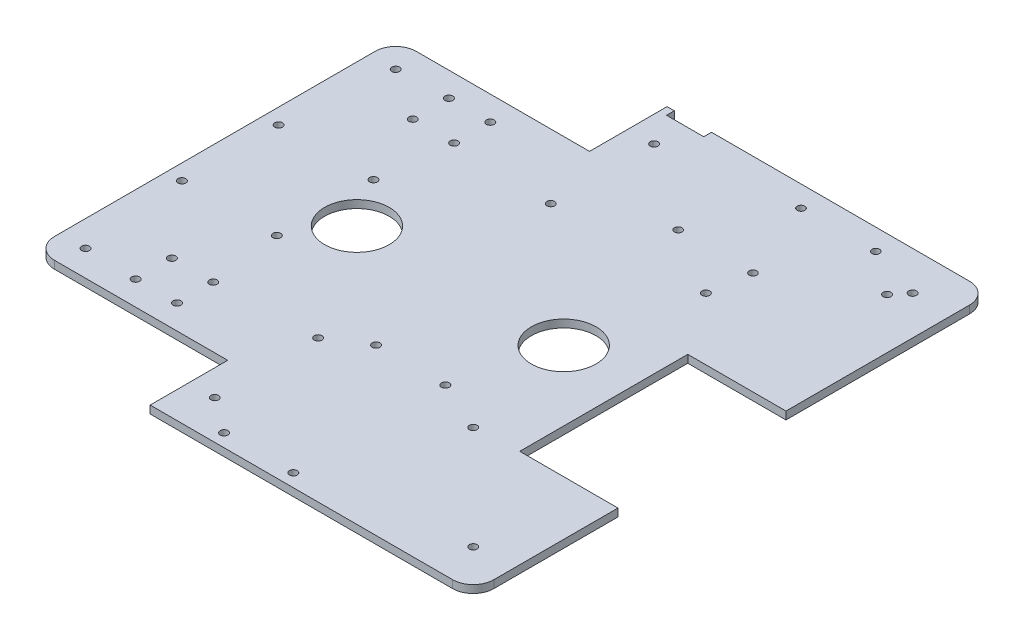
SolidWorks part; units mm, degrees
ref_plane "Front Plane" through (0, 0, 0) normal (0, 0, 1) x (1, 0, 0)
ref_plane "Top Plane" through (0, 0, 0) normal (0, 1, 0) x (1, 0, 0)
ref_plane "Right Plane" through (0, 0, 0) normal (1, 0, 0) x (0, 0, -1)
sketch "Sketch1" plane through (0, 0, 0) normal (0, 1, 0) x (1, 0, 0)
  line L1 (-100, 100) -> (100, 100)
  line L2 (-100, 100) -> (-100, -100)
  line L3 (-100, -100) -> (100, -100)
  line L4 (100, 100) -> (100, -100)
  line L5 (-100, 100) -> (100, -100) construction
  line L6 (-100, -100) -> (100, 100) construction
  point P0 (0, 0)
  dimension "D1" = 200
  dimension "D2" = 200
extrude "Boss-Extrude1" add sketch "Sketch1" along normal blind 3
sketch "Sketch4" plane through (0, 0, 0) normal (0, -1, 0) x (1, 0, 0)
  line L0 (100, 100) -> (100, -100) construction
  circle A0 centre (-15, 45) radius 1.5
  circle A1 centre (45, 45) radius 1.5
  circle A2 centre (45, -45) radius 1.5
  circle A3 centre (-15, -45) radius 1.5
  dimension "D1" = 3
  dimension "D2" = 3
  dimension "D3" = 3
  dimension "D4" = 3
  dimension "D8" = 55
  dimension "D5" = 60
  dimension "D6" = 90
  dimension "D7" = 45
extrude "Cut-Extrude4" cut sketch "Sketch4" against normal up to next
sketch "Sketch5" plane through (0, 0, 0) normal (0, -1, 0) x (1, 0, 0)
  line L1 (-100, -70) -> (-25, -70)
  line L2 (-100, -70) -> (-100, -100)
  line L3 (-100, -100) -> (-25, -100)
  line L4 (-25, -70) -> (-25, -100)
  line L5 (-100, -70) -> (-25, -100) construction
  line L6 (-100, -100) -> (-25, -70) construction
  line L8 (-100, 100) -> (-25, 100)
  line L9 (-100, 100) -> (-100, 70)
  line L10 (-100, 70) -> (-25, 70)
  line L11 (-25, 100) -> (-25, 70)
  line L12 (-100, 100) -> (-25, 70) construction
  line L13 (-100, 70) -> (-25, 100) construction
  point P0 (-62.5, -85)
  point P6 (-62.5, 85)
  dimension "D1" = 75
  dimension "D2" = 30
  dimension "D3" = 75
  dimension "D4" = 30
extrude "Cut-Extrude5" cut sketch "Sketch5" against normal up to next and the other way through all
sketch "Sketch3" plane through (0, 0, 0) normal (0, -1, 0) x (1, 0, 0)
  line L0 (-100, 70) -> (-25, 70) construction
  line L1 (-25, -70) -> (-100, -70) construction
  line L2 (-100, -70) -> (-100, 70) construction
  circle A0 centre (-70, -60.6) radius 1.5
  circle A1 centre (-70, -46.6) radius 1.5
  circle A2 centre (-54, -46.6) radius 1.5
  circle A3 centre (-54, -60.6) radius 1.5
  circle A4 centre (-70, 60.6) radius 1.5
  circle A5 centre (-54, 60.6) radius 1.5
  circle A6 centre (-70, 46.6) radius 1.5
  circle A7 centre (-54, 46.6) radius 1.5
  dimension "D1" = 3
  dimension "D2" = 3
  dimension "D3" = 3
  dimension "D4" = 3
  dimension "D5" = 3
  dimension "D6" = 3
  dimension "D7" = 3
  dimension "D8" = 3
  dimension "D9" = 16
  dimension "D10" = 14
  dimension "D11" = 14
  dimension "D12" = 9.4
  dimension "D13" = 9.4
  dimension "D14" = 30
extrude "Cut-Extrude6" cut sketch "Sketch3" against normal up to next
fillet "Fillet1" radius 8 4 edges at (100, 1.5, -100) (100, 1.5, 100) (-100, 1.5, 70) (-100, 1.5, -70)
sketch "Sketch6" plane through (0, 0, 0) normal (0, -1, 0) x (1, 0, 0)
  line L0 (-92, 70) -> (-25, 70) construction
  line L1 (-100, -62) -> (-100, 62) construction
  line L2 (-25, -70) -> (-92, -70) construction
  line L3 (-25, -100) -> (-25, -70) construction
  line L4 (92, -100) -> (-25, -100) construction
  line L5 (100, 92) -> (100, -92) construction
  line L6 (-25, 100) -> (92, 100) construction
  line L7 (-25, 70) -> (-25, 100) construction
  circle A0 centre (-90, 60) radius 1.5
  circle A1 centre (-90, -60) radius 1.5
  circle A2 centre (-15, -85) radius 1.5
  circle A3 centre (85, -85) radius 1.5
  circle A4 centre (85, 85) radius 1.5
  circle A5 centre (-15, 85) radius 1.5
  dimension "D1" = 3
  dimension "D2" = 3
  dimension "D3" = 3
  dimension "D4" = 3
  dimension "D5" = 3
  dimension "D6" = 3
  dimension "D7" = 10
  dimension "D8" = 10
  dimension "D9" = 10
  dimension "D10" = 10
  dimension "D11" = 10
  dimension "D12" = 15
  dimension "D13" = 15
  dimension "D14" = 15
  dimension "D15" = 15
  dimension "D16" = 10
extrude "Cut-Extrude7" cut sketch "Sketch6" against normal up to next
sketch "Sketch9" plane through (0, 3, 0) normal (0, 1, 0) x (1, 0, 0)
  line L0 (100, -92) -> (100, 92) construction
  point P0 (100, 0)
sketch "Sketch11" plane through (0, 0, 0) normal (0, 1, 0) x (1, 0, 0)
  line L0 (-25, -100) -> (92, -100) construction
  line L1 (62, -44) -> (100, -44)
  line L2 (62, -44) -> (62, 21)
  line L3 (62, 21) -> (100, 21)
  line L4 (100, -44) -> (100, 21)
  line L5 (62, -44) -> (100, 21) construction
  line L6 (62, 21) -> (100, -44) construction
  line L7 (100, -92) -> (100, 92) construction
  point P0 (81, -11.5)
  dimension "D1" = 56
  dimension "D2" = 38
  dimension "D3" = 65
extrude "Cut-Extrude9" cut sketch "Sketch11" along normal up to next
sketch "Sketch12" plane through (0, 0, 0) normal (0, -1, 0) x (-1, 0, 0)
  circle A1 centre (-35, 0) radius 12.5
  circle A2 centre (45, 0) radius 12.5
  dimension "D1" = 25
  dimension "D2" = 25
  dimension "D3" = 45
  dimension "D4" = 35
extrude "Cut-Extrude10" cut sketch "Sketch12" against normal up to next
sketch "Sketch13" plane through (0, 3, 0) normal (0, 1, 0) x (1, 0, 0)
  line L0 (-122.3148, 0) -> (118.4141, 0) construction
sketch "Sketch14" plane through (0, 0, 0) normal (0, -1, 0) x (-1, 0, 0)
  line L0 (122.3148, 0) -> (-118.4141, 0) construction
  line L1 (100, 62) -> (100, -62) construction
  circle A0 centre (94, 18.7) radius 1.5
  circle A1 centre (94, -18.7) radius 1.5
  circle A2 centre (57.3, -18.7) radius 1.5
  circle A3 centre (57.3, 18.7) radius 1.5
  dimension "D1" = 3
  dimension "D2" = 3
  dimension "D3" = 3
  dimension "D4" = 3
  dimension "D5" = 37.4
  dimension "D6" = 36.7
  dimension "D7" = 18.7
  dimension "D8" = 6
extrude "Cut-Extrude11" cut sketch "Sketch14" against normal up to next
sketch "Sketch15" plane through (0, 0, 0) normal (0, -1, 0) x (-1, 0, 0)
  line L0 (25, -70) -> (25, -100) construction
  line L1 (25, -100) -> (-92, -100) construction
  circle A0 centre (1.4, -95) radius 1.5
  circle A1 centre (-25.4, -95) radius 1.5
  circle A2 centre (-25.4, -36.2) radius 1.5
  circle A3 centre (1.4, -36.2) radius 1.5
  dimension "D1" = 3
  dimension "D2" = 3
  dimension "D3" = 3
  dimension "D4" = 3
  dimension "D5" = 26.8
  dimension "D6" = 58.8
  dimension "D7" = 23.6
  dimension "D8" = 5
extrude "Cut-Extrude12" cut sketch "Sketch15" against normal up to next
sketch "Sketch17" plane through (0, 3, 0) normal (0, 1, 0) x (1, 0, 0)
  circle A0 centre (63.8888, 91.851) radius 1.4605
  circle A1 centre (47.3661, 60.8512) radius 1.4605
  circle A2 centre (34.9628, 91.851) radius 1.4605
  circle A3 centre (18.4401, 60.8512) radius 1.4605
  circle A4 centre (18.4401, 60.8512) radius 1.4605 construction
  circle A5 centre (34.9628, 91.851) radius 1.4605 construction
  circle A6 centre (63.8888, 91.851) radius 1.4605 construction
  circle A7 centre (47.3661, 60.8512) radius 1.4605 construction
extrude "Cut-Extrude14" cut sketch "Sketch17" against normal up to next
sketch "Sketch18" plane through (0, 3, 0) normal (0, 1, 0) x (1, 0, 0)
  circle A0 centre (80.5, 79.6132) radius 1.5
  circle A1 centre (80.5, 79.6132) radius 1.5 construction
extrude "Cut-Extrude15" cut sketch "Sketch18" against normal up to next contours A0
sketch "Sketch19" plane through (0, 3, 0) normal (0, 1, 0) x (1, 0, 0)
  line L0 (92, 100) -> (-25, 100) construction
  line L1 (-5, 97) -> (-25, 97)
  line L2 (-5, 97) -> (-5, 100)
  line L3 (-5, 100) -> (-25, 100)
  line L4 (-25, 97) -> (-25, 100)
  line L5 (-5, 97) -> (-25, 100) construction
  line L6 (-5, 100) -> (-25, 97) construction
  line L7 (-7.8, 100) -> (-7.8, 97)
  line L8 (-22.2, 97) -> (-22.2, 100)
  point P0 (-15, 98.5)
  dimension "D1" = 75
  dimension "D2" = 3
  dimension "D3" = 20
  dimension "D4" = 2.8
  dimension "3" = 2.8
extrude "Cut-Extrude17" cut sketch "Sketch19" against normal up to next contours L8 L1 L7 L3
